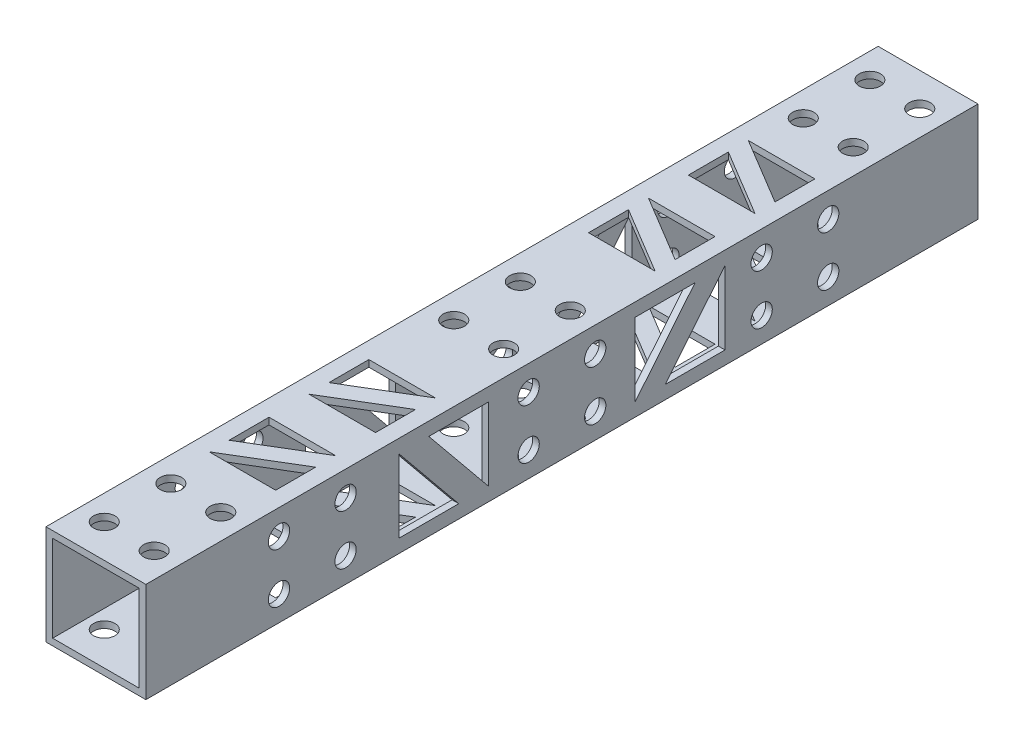
SolidWorks part; units mm, degrees
ref_plane "前视基准面" through (0, 0, 0) normal (0, 0, 1) x (1, 0, 0)
ref_plane "上视基准面" through (0, 0, 0) normal (0, 1, 0) x (1, 0, 0)
ref_plane "右视基准面" through (0, 0, 0) normal (1, 0, 0) x (0, 0, -1)
other "Configuration Table"
sketch "草图1" plane through (0, 0, 0) normal (0, 0, 1) x (1, 0, 0)
  line L1 (0, 0) -> (15, 0)
  line L2 (0, 0) -> (0, -15)
  line L3 (0, -15) -> (15, -15)
  line L4 (15, 0) -> (15, -15)
  dimension "D1" = 15
  dimension "D2" = 15
extrude "拉伸-薄壁1" add sketch "草图1" along normal blind 125 thin
sketch "草图2" plane through (15, 0, 0) normal (1, 0, 0) x (0, 0, -1)
  line L0 (-45, 0) -> (-45, -15) construction
  line L1 (-125, 0) -> (0, 0) construction
  line L2 (-125, -15) -> (0, -15) construction
  line L3 (-100, 0) -> (-100, -15) construction
  line L4 (-125, -15) -> (-125, 0) construction
  line L5 (-125, -7.5) -> (-100, -7.5) construction
  line L6 (-27.5, 0) -> (-27.5, -15) construction
  line L7 (0, -7.5) -> (-27.5, -7.5) construction
  line L8 (0, -15) -> (0, 0) construction
  line L9 (-80, -7.5) -> (-100, -7.5) construction
  line L21 (-87, -2) -> (-87, -13)
  line L22 (-87, -13) -> (-78, -13)
  line L23 (-78, -13) -> (-87, -2)
  line L25 (-82.5, -2) -> (-73.5, -2)
  line L26 (-73.5, -2) -> (-73.5, -13)
  line L27 (-73.5, -13) -> (-82.5, -2)
  line L35 (-62.5, 0) -> (-62.5, -15) construction
  line L37 (-51.5, -13) -> (-42.5, -2)
  line L38 (-51.5, -2) -> (-51.5, -13)
  line L39 (-42.5, -2) -> (-51.5, -2)
  line L40 (-47, -13) -> (-38, -2)
  line L41 (-38, -13) -> (-47, -13)
  line L42 (-38, -2) -> (-38, -13)
  circle A0 centre (-105, -3.75) radius 1.6
  circle A1 centre (-105, -11.25) radius 1.6
  circle A2 centre (-95, -11.25) radius 1.6
  circle A3 centre (-95, -3.75) radius 1.6
  circle A8 centre (-22.5, -3.75) radius 1.6
  circle A9 centre (-22.5, -11.25) radius 1.6
  circle A10 centre (-32.5, -11.25) radius 1.6
  circle A11 centre (-32.5, -3.75) radius 1.6
  circle A15 centre (-57.5, -11.25) radius 1.6
  circle A16 centre (-67.5, -11.25) radius 1.6
  circle A17 centre (-67.5, -3.75) radius 1.6
  circle A18 centre (-57.5, -3.75) radius 1.6
  dimension "D2" = 3.2
  dimension "D6" = 3.2
  dimension "D11" = 11
  dimension "D1" = 25
  dimension "D3" = 5
  dimension "D4" = 3.75
  dimension "D5" = 17.5
  dimension "D7" = 3.75
  dimension "D8" = 5
  dimension "D9" = 9
  dimension "D10" = 20
  dimension "D12" = 9
  dimension "D13" = 11
  dimension "D14" = 45
  dimension "D15" = 13
  dimension "D16" = 6
extrude "切除-拉伸1" cut sketch "草图2" against normal through all
sketch "草图3" plane through (0, 0, 0) normal (0, 1, 0) x (1, 0, 0)
  line L0 (7.5, 0) -> (7.5, -125) construction
  line L1 (15, 0) -> (0, 0) construction
  line L2 (15, -125) -> (0, -125) construction
  line L3 (15, -62.5) -> (0, -62.5) construction
  line L4 (15, -125) -> (15, 0) construction
  line L5 (0, -125) -> (0, 0) construction
  line L6 (0, -10) -> (15, -10) construction
  line L7 (0, -115) -> (15, -115) construction
  line L8 (2.5, -25) -> (2.5, -31)
  line L9 (2.5, -31) -> (12.5, -31)
  line L10 (12.5, -31) -> (2.5, -25)
  line L11 (2.5, -22) -> (12.5, -22)
  line L12 (12.5, -22) -> (12.5, -28)
  line L13 (12.5, -28) -> (2.5, -22)
  line L14 (2.5, -37) -> (12.5, -37)
  line L15 (12.5, -37) -> (12.5, -43)
  line L16 (12.5, -43) -> (2.5, -37)
  line L17 (12.5, -46) -> (2.5, -40)
  line L18 (2.5, -40) -> (2.5, -46)
  line L19 (2.5, -46) -> (12.5, -46)
  line L20 (2.5, -79) -> (12.5, -79)
  line L21 (2.5, -85) -> (2.5, -79)
  line L22 (12.5, -79) -> (2.5, -85)
  line L23 (12.5, -82) -> (2.5, -88)
  line L24 (12.5, -88) -> (12.5, -82)
  line L25 (2.5, -88) -> (12.5, -88)
  line L26 (12.5, -97) -> (2.5, -103)
  line L27 (12.5, -103) -> (12.5, -97)
  line L28 (2.5, -103) -> (12.5, -103)
  line L29 (12.5, -94) -> (2.5, -100)
  line L30 (2.5, -94) -> (12.5, -94)
  line L31 (2.5, -100) -> (2.5, -94)
  circle A0 centre (3.75, -5) radius 1.6
  circle A1 centre (11.25, -5) radius 1.6
  circle A2 centre (11.25, -15) radius 1.6
  circle A3 centre (3.75, -15) radius 1.6
  circle A16 centre (3.75, -57.5) radius 1.6
  circle A17 centre (11.25, -57.5) radius 1.6
  circle A18 centre (11.25, -67.5) radius 1.6
  circle A19 centre (3.75, -67.5) radius 1.6
  circle A28 centre (3.75, -110) radius 1.6
  circle A29 centre (11.25, -110) radius 1.6
  circle A30 centre (11.25, -120) radius 1.6
  circle A31 centre (3.75, -120) radius 1.6
  dimension "D1" = 3.2
  dimension "D7" = 3.2
  dimension "D2" = 3.75
  dimension "D3" = 10
  dimension "D4" = 5
  dimension "D6" = 10
  dimension "D8" = 5
  dimension "D9" = 3.75
  dimension "D5" = 6
  dimension "D10" = 10
  dimension "D11" = 6
  dimension "D12" = 15
  dimension "12" = 12
  dimension "D13" = 9
  dimension "D14" = 2
extrude "切除-拉伸2" cut sketch "草图3" against normal through all
